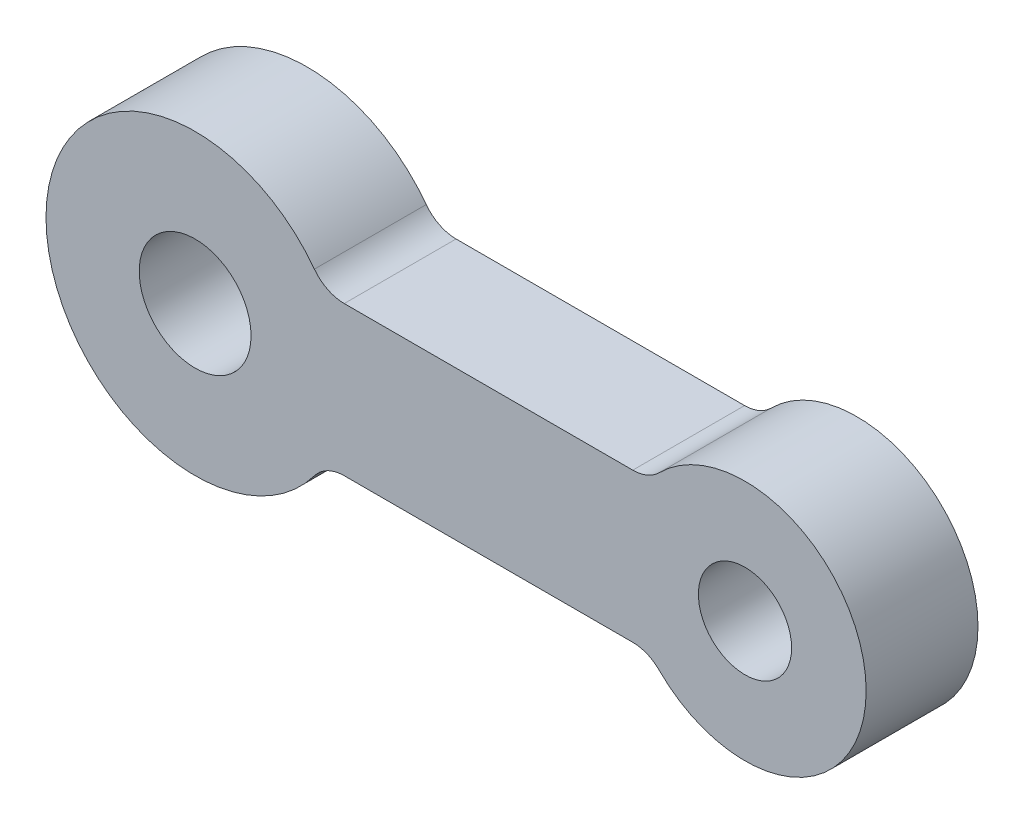
SolidWorks part; units mm, degrees
ref_plane "Plan de face" through (0, 0, 0) normal (0, 0, 1) x (1, 0, 0)
ref_plane "Plan de dessus" through (0, 0, 0) normal (0, 1, 0) x (1, 0, 0)
ref_plane "Plan de droite" through (0, 0, 0) normal (1, 0, 0) x (0, 0, -1)
sketch "Esquisse1" plane through (0, 0, 0) normal (0, 0, 1) x (1, 0, 0)
  line L0 (0, 0) -> (29.5, 0) construction
  line L1 (6.9282, 4) -> (24.3765, 4)
  line L2 (0, 0) -> (-8, 0) construction
  line L3 (36, 0) -> (29.5, 0) construction
  line L4 (6.9282, -4) -> (24.3765, -4)
  circle A0 centre (0, 0) radius 3
  circle A1 centre (29.5, 0) radius 2.5
  arc A2 (6.9282, -4) -> (6.9282, 4) centre (0, 0) cw
  arc A3 (24.3765, 4) -> (24.3765, -4) centre (29.5, 0) cw
  point P10 (0, 0)
  dimension "D1" = 6
  dimension "D2" = 5
  dimension "D4" = 8
  dimension "D6" = 6.5
  dimension "D3" = 29.5
  dimension "D5" = 4
extrude "Boss.-Extru.1" add sketch "Esquisse1" along normal blind 6
fillet "Congé1" radius 2 4 edges at (6.9282, 4, 3) (24.3765, 4, 3) (24.3765, -4, 3) (6.9282, -4, 3)
